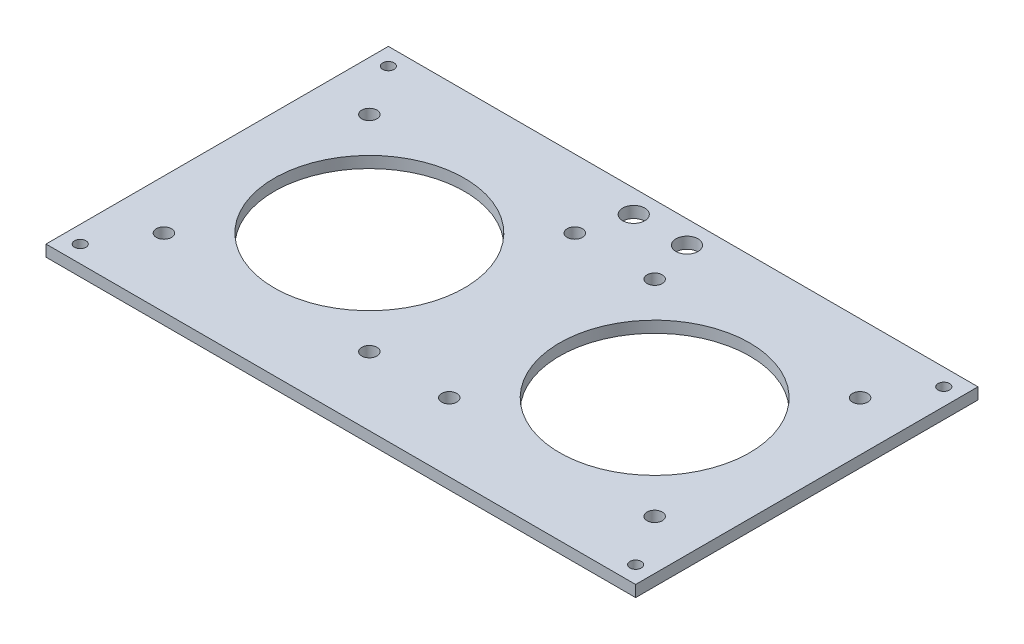
SolidWorks part; units mm, degrees
ref_plane "Plan de face" through (0, 0, 0) normal (0, 0, 1) x (1, 0, 0)
ref_plane "Plan de dessus" through (0, 0, 0) normal (0, 1, 0) x (1, 0, 0)
ref_plane "Plan de droite" through (0, 0, 0) normal (1, 0, 0) x (0, 0, -1)
sketch "Esquisse1" plane through (0, 0, 0) normal (0, 1, 0) x (1, 0, 0)
  line L0 (-37.5, 45) -> (-37.5, -45) construction
  line L1 (-77.5, -45) -> (77.5, -45)
  line L2 (-77.5, -45) -> (-77.5, 45)
  line L3 (-77.5, 45) -> (77.5, 45)
  line L4 (77.5, -45) -> (77.5, 45)
  line L5 (-77.5, -45) -> (77.5, 45) construction
  line L6 (-77.5, 45) -> (77.5, -45) construction
  line L7 (-77.5, 0) -> (77.5, 0) construction
  line L8 (0, 45) -> (0, -45) construction
  circle A0 centre (-37.5, 0) radius 25
  circle A1 centre (-64.5, 27) radius 2
  circle A2 centre (-10.5, 27) radius 2
  circle A3 centre (-10.5, -27) radius 2
  circle A4 centre (-64.5, -27) radius 2
  circle A5 centre (10.5, -27) radius 2
  circle A6 centre (64.5, -27) radius 2
  circle A7 centre (64.5, 27) radius 2
  circle A8 centre (10.5, 27) radius 2
  circle A9 centre (37.5, 0) radius 25
  circle A10 centre (-73, 40.5) radius 1.5
  circle A11 centre (73, 40.5) radius 1.5
  circle A12 centre (73, -40.5) radius 1.5
  circle A13 centre (-73, -40.5) radius 1.5
  circle A14 centre (-7, 39) radius 2.9
  circle A15 centre (7, 39) radius 2.9
  point P0 (0, 0)
  point P14 (0, 0)
  point P38 (73, -40.5)
  dimension "D3" = 50
  dimension "D6" = 4
  dimension "D10" = 3
  dimension "D12" = 7
  dimension "D11" = 5.8
  dimension "D1" = 155
  dimension "D2" = 90
  dimension "D4" = 40
  dimension "D5" = 27
  dimension "D7" = 27
  dimension "D8" = 4.5
  dimension "D9" = 4.5
  dimension "D13" = 6
extrude "Boss.-Extru.1" add sketch "Esquisse1" along normal blind 3
